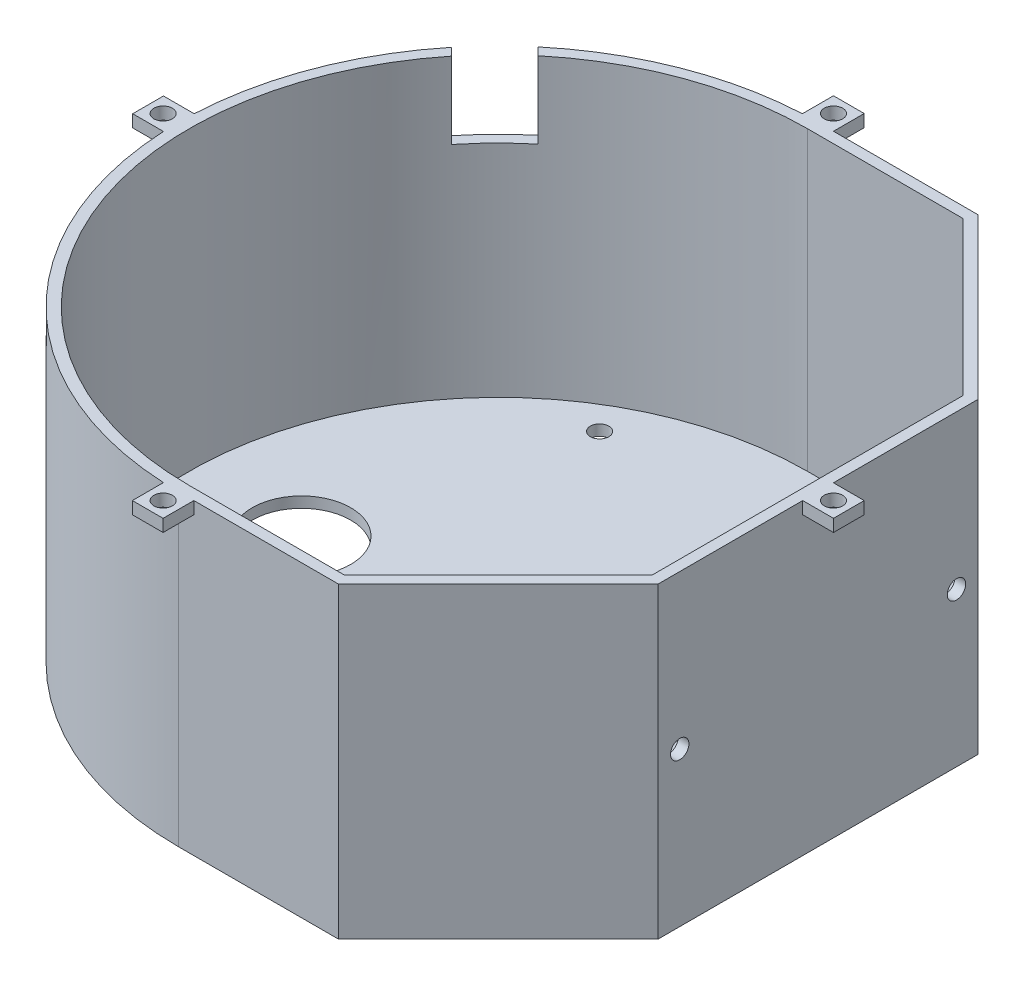
SolidWorks part; units mm, degrees
ref_plane "前视基准面" through (0, 0, 0) normal (0, 0, 1) x (1, 0, 0)
ref_plane "上视基准面" through (0, 0, 0) normal (0, 1, 0) x (1, 0, 0)
ref_plane "右视基准面" through (0, 0, 0) normal (1, 0, 0) x (0, 0, -1)
sketch "草图1" plane through (0, 0, 0) normal (0, 1, 0) x (1, 0, 0)
  line L0 (0, -52) -> (26, -52)
  line L1 (52, -26) -> (52, 26)
  line L2 (0, 52) -> (26, 52)
  line L3 (26, -52) -> (52, -26)
  line L4 (26, 52) -> (52, 26)
  arc A5 (0, -52) -> (0, 52) centre (0, 0) cw
extrude "凸台-拉伸5" add sketch "草图1" along normal blind 50
shell "抽壳4" thickness 1.75
sketch "草图3" plane through (0, 1.75, 0) normal (0, 1, 0) x (1, 0, 0)
  circle A3 centre (-32, 0) radius 8
  circle A4 centre (45, 0) radius 1.5
  circle A7 centre (-22.5, 38.9711) radius 1.5
  circle A8 centre (-22.5, -38.9711) radius 1.5
  dimension "D1" = 32
  dimension "D2" = 45
extrude "切除-拉伸2" cut sketch "草图3" against normal blind 5
ref_plane "相机基准面" through (52, 0, 0) normal (1, 0, 0) x (0, 0, -1)
sketch "草图5" plane through (52, 0, 0) normal (1, 0, 0) x (0, 0, -1)
  line L0 (0, 50) -> (0, 0) construction
  line L3 (0, 25) -> (55.4448, 25) construction
  circle A0 centre (22.5, 25) radius 1.5
  circle A1 centre (-22.5, 25) radius 1.5
  dimension "D1" = 22.5
extrude "切除-拉伸3" cut sketch "草图5" against normal blind 5
ref_plane "基准面2" through (0, 50, 0) normal (0, 1, 0) x (1, 0, 0)
sketch "草图6" plane through (0, 50, 0) normal (0, 1, 0) x (1, 0, 0)
  line L0 (0, 0) -> (67.3689, 0) construction
  line L1 (0, 0) -> (0, -12.8109) construction
  line L2 (52, -27.5) -> (52, 27.5) construction
  line L3 (52, 2.5) -> (57, 2.5)
  line L4 (52, 2.5) -> (52, -2.5)
  line L5 (52, -2.5) -> (57, -2.5)
  line L6 (57, 2.5) -> (57, -2.5)
  line L7 (52, 2.5) -> (57, -2.5) construction
  line L8 (52, -2.5) -> (57, 2.5) construction
  line L9 (-51.9399, 2.5) -> (-56.9399, 2.5)
  line L14 (26, 52) -> (0, 52) construction
  line L22 (-56.9399, 2.5) -> (-56.9399, -2.5)
  line L23 (-56.9399, -2.5) -> (-51.9399, -2.5)
  line L24 (-51.9399, 2.5) -> (-51.9399, -2.5)
  line L29 (0, -52) -> (26, -52) construction
  line L33 (2.5, 52) -> (2.5, 57)
  line L34 (2.5, 57) -> (-2.5, 57)
  line L35 (-2.5, 52) -> (-2.5, 57)
  line L36 (2.5, 52) -> (-2.5, 57) construction
  line L37 (2.5, 57) -> (-2.5, 52) construction
  line L40 (-2.5, 52) -> (-2.5, 51.6335)
  line L49 (2.5, -57) -> (-2.5, -57)
  line L50 (2.5, -57) -> (2.5, -51.4602)
  line L55 (2.5, -51.4602) -> (-2.5, -51.4602)
  line L56 (-2.5, -57) -> (-2.5, -51.4602)
  line L57 (2.5, -57) -> (-2.5, -51.4602) construction
  line L58 (2.5, -51.4602) -> (-2.5, -57) construction
  line L59 (-2.5, 51.6335) -> (2.5, 51.6335)
  line L60 (2.5, 51.6335) -> (2.5, 52)
  arc A0 (0, 52) -> (0, -52) centre (0, 0) ccw construction
  circle A2 centre (54.5, 0) radius 1.5
  circle A4 centre (-54.5, 0) radius 1.5
  circle A5 centre (0, -54.5) radius 1.5
  circle A6 centre (0, 54.5) radius 1.5
  point P9 (54.5, 0)
  point P22 (0, -54.5)
  point P32 (0, 54.5)
  point P38 (-56.9399, 0)
  point P39 (0, -52)
  point P40 (0, -54.2301)
  point P47 (0, 51.6482)
  point P48 (0, -51.4602)
  point P49 (0, 51.6335)
  dimension "D9" = 56.9399
  dimension "D1" = 0
  dimension "D2" = 2.5
  dimension "D3" = 5
  dimension "D4" = 5
  dimension "D5" = 0
  dimension "D6" = 5
  dimension "D7" = 5
  dimension "D8" = 5
  dimension "D10" = 5
  dimension "D11" = 0
  dimension "D12" = 2.5
  dimension "D13" = 54.5
  dimension "D14" = 54.5
  dimension "D15" = 54.5
extrude "凸台-拉伸8" add sketch "草图6" against normal blind 2
ref_plane "基准面3" through (-29.7514, 0, -29.7185) normal (-0.7075, 0, -0.7067) x (-0.7067, 0, 0.7075)
sketch "草图9" plane through (-29.7514, 0, -29.7185) normal (-0.7075, 0, -0.7067) x (-0.7067, 0, 0.7075)
  line L1 (-4.6218, 51.8082) -> (5.3238, 51.8082)
  line L2 (-4.6218, 51.8082) -> (-4.6218, 37.5618)
  line L3 (-4.6218, 37.5618) -> (5.3238, 37.5618)
  line L4 (5.3238, 51.8082) -> (5.3238, 37.5618)
  line L5 (-4.6218, 51.8082) -> (5.3238, 37.5618) construction
  line L6 (-4.6218, 37.5618) -> (5.3238, 51.8082) construction
  point P4 (0.351, 44.685)
extrude "切除-拉伸4" cut sketch "草图9" along normal blind 15
